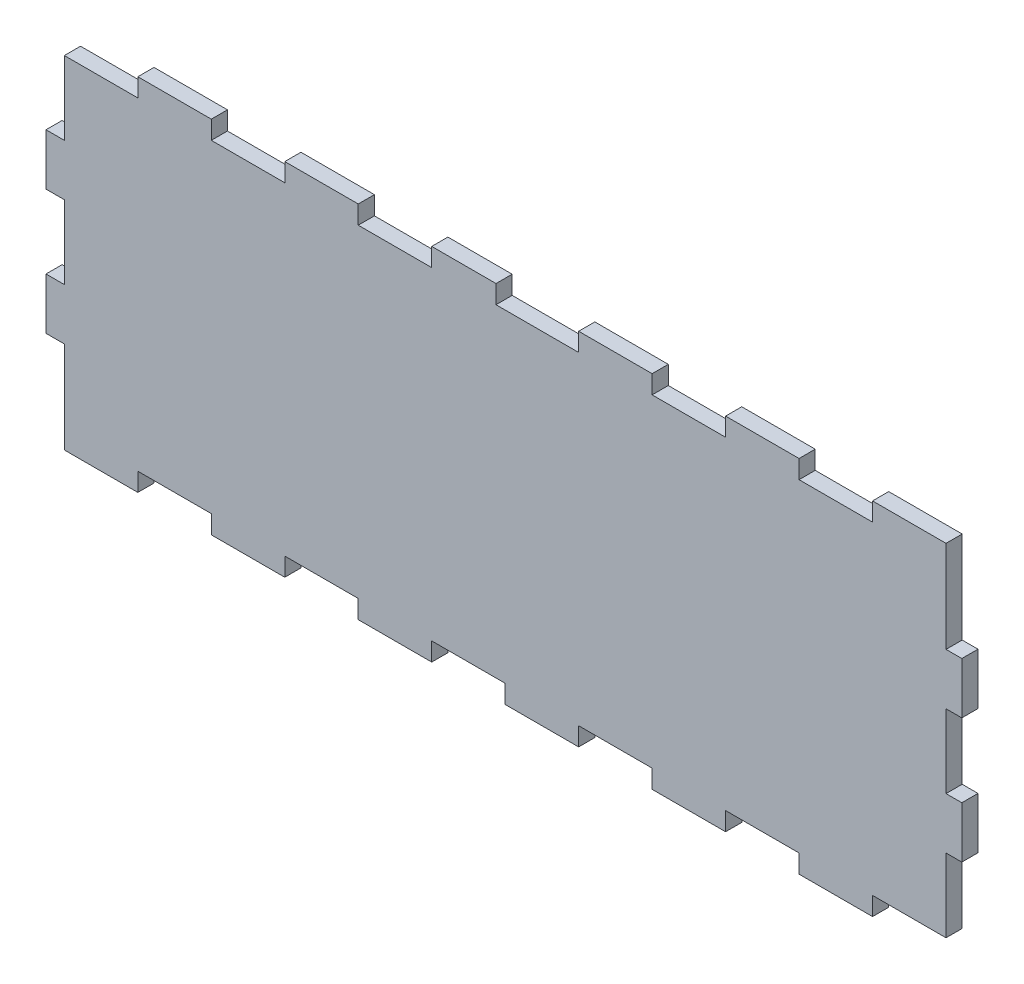
SolidWorks part; units mm, degrees
ref_plane "Front Plane" through (0, 0, 0) normal (0, 0, 1) x (1, 0, 0)
ref_plane "Top Plane" through (0, 0, 0) normal (0, 1, 0) x (1, 0, 0)
ref_plane "Right Plane" through (0, 0, 0) normal (1, 0, 0) x (0, 0, -1)
sketch "Sketch1" plane through (-5.3296, -16.203, 0) normal (0, 0, 1) x (1, 0, 0)
  line L0 (-139.4125, -47.1311) -> (-139.4125, -165.2411) construction
  line L1 (-294.9875, -47.1311) -> (-294.9875, -40.7811) construction
  line L2 (-294.9875, -47.1311) -> (-294.9875, -165.2411)
  line L3 (-294.9875, -165.2411) -> (16.1625, -165.2411)
  line L4 (16.1625, -158.8911) -> (16.1625, -165.2411)
  line L5 (-139.4125, -47.1311) -> (16.1625, -47.1311)
  line L6 (-294.9875, -158.8911) -> (16.1625, -158.8911)
  line L7 (16.1625, -47.1311) -> (16.1625, -158.8911)
  line L8 (-139.4125, -47.1311) -> (-294.9875, -47.1311)
  line L9 (-139.4125, -40.7811) -> (16.1625, -40.7811)
  line L10 (16.1625, -40.7811) -> (16.1625, -47.1311)
  line L11 (-139.4125, -47.1311) -> (-139.4125, -40.7811)
  line L12 (-139.4125, -40.7811) -> (-288.6375, -40.7811)
  line L13 (-288.6375, -165.2411) -> (-288.6375, -40.7811)
  line L14 (-136.2375, -47.1311) -> (-139.4125, -47.1311)
  line L15 (16.1625, -47.1311) -> (21.6327, -47.1311)
  line L16 (16.1625, -47.1311) -> (16.1625, -158.8911)
  line L17 (16.1625, -158.8911) -> (21.6327, -158.8911)
  line L18 (21.6327, -47.1311) -> (21.6327, -158.8911)
  line L19 (16.1625, -47.1311) -> (21.6327, -47.1311)
  line L20 (16.1625, -47.1311) -> (16.1625, -72.5311)
  line L21 (-288.6375, -165.2411) -> (-263.2375, -165.2411)
  line L22 (-288.6375, -165.2411) -> (-288.6375, -158.8911)
  line L23 (-288.6375, -158.8911) -> (-263.2375, -158.8911)
  line L24 (-263.2375, -165.2411) -> (-263.2375, -158.8911)
  line L25 (-237.8375, -158.8911) -> (-212.4375, -158.8911)
  line L26 (-237.8375, -158.8911) -> (-237.8375, -165.2411)
  line L27 (-237.8375, -165.2411) -> (-212.4375, -165.2411)
  line L28 (-212.4375, -158.8911) -> (-212.4375, -165.2411)
  line L29 (-187.0375, -158.8911) -> (-161.6375, -158.8911)
  line L30 (-187.0375, -158.8911) -> (-187.0375, -165.2411)
  line L31 (-187.0375, -165.2411) -> (-161.6375, -165.2411)
  line L32 (-161.6375, -158.8911) -> (-161.6375, -165.2411)
  line L33 (-136.2375, -158.8911) -> (-110.8375, -158.8911)
  line L34 (-136.2375, -158.8911) -> (-136.2375, -165.2411)
  line L35 (-136.2375, -165.2411) -> (-110.8375, -165.2411)
  line L36 (-110.8375, -158.8911) -> (-110.8375, -165.2411)
  line L37 (-85.4375, -158.8911) -> (-60.0375, -158.8911)
  line L38 (-85.4375, -158.8911) -> (-85.4375, -165.2411)
  line L39 (-85.4375, -165.2411) -> (-60.0375, -165.2411)
  line L40 (-60.0375, -158.8911) -> (-60.0375, -165.2411)
  line L41 (-34.6375, -158.8911) -> (-9.2375, -158.8911)
  line L42 (-34.6375, -158.8911) -> (-34.6375, -165.2411)
  line L43 (-34.6375, -165.2411) -> (-9.2375, -165.2411)
  line L44 (-9.2375, -158.8911) -> (-9.2375, -165.2411)
  line L45 (-294.9875, -47.1311) -> (-288.6375, -47.1311)
  line L46 (-294.9875, -47.1311) -> (-294.9875, -72.5311)
  line L47 (-294.9875, -72.5311) -> (-288.6375, -72.5311)
  line L48 (-288.6375, -47.1311) -> (-288.6375, -72.5311)
  line L49 (-294.9875, -90.3111) -> (-288.6375, -90.3111)
  line L50 (-294.9875, -90.3111) -> (-294.9875, -115.7111)
  line L51 (-294.9875, -115.7111) -> (-288.6375, -115.7111)
  line L52 (-288.6375, -90.3111) -> (-288.6375, -115.7111)
  line L53 (-294.9875, -133.4911) -> (-288.6375, -133.4911)
  line L54 (-294.9875, -133.4911) -> (-294.9875, -158.8911)
  line L55 (-294.9875, -158.8911) -> (-288.6375, -158.8911)
  line L56 (-288.6375, -133.4911) -> (-288.6375, -158.8911)
  line L57 (16.1625, -72.5311) -> (21.6327, -72.5311)
  line L58 (21.6327, -47.1311) -> (21.6327, -72.5311)
  line L59 (16.1625, -90.3111) -> (21.6327, -90.3111)
  line L60 (16.1625, -90.3111) -> (16.1625, -115.7111)
  line L61 (16.1625, -115.7111) -> (21.6327, -115.7111)
  line L62 (21.6327, -90.3111) -> (21.6327, -115.7111)
  line L63 (21.6327, -158.8911) -> (16.1625, -158.8911)
  line L64 (21.6327, -158.8911) -> (21.6327, -133.4911)
  line L65 (21.6327, -133.4911) -> (16.1625, -133.4911)
  line L66 (16.1625, -158.8911) -> (16.1625, -133.4911)
  line L67 (-288.6375, -40.7811) -> (-263.2375, -40.7811)
  line L68 (-288.6375, -40.7811) -> (-288.6375, -47.1311)
  line L69 (-288.6375, -47.1311) -> (-263.2375, -47.1311)
  line L70 (-263.2375, -40.7811) -> (-263.2375, -47.1311)
  line L71 (-237.8375, -40.7811) -> (-212.4375, -40.7811)
  line L72 (-237.8375, -40.7811) -> (-237.8375, -47.1311)
  line L73 (-237.8375, -47.1311) -> (-212.4375, -47.1311)
  line L74 (-212.4375, -40.7811) -> (-212.4375, -47.1311)
  line L75 (-187.0375, -40.7811) -> (-161.6375, -40.7811)
  line L76 (-187.0375, -40.7811) -> (-187.0375, -47.1311)
  line L77 (-187.0375, -47.1311) -> (-161.6375, -47.1311)
  line L78 (-161.6375, -40.7811) -> (-161.6375, -47.1311)
  line L79 (-136.2375, -40.7811) -> (-110.8375, -40.7811)
  line L80 (-136.2375, -40.7811) -> (-136.2375, -47.1311)
  line L81 (-136.2375, -47.1311) -> (-110.8375, -47.1311)
  line L82 (-110.8375, -40.7811) -> (-110.8375, -47.1311)
  line L83 (-85.4375, -40.7811) -> (-60.0375, -40.7811)
  line L84 (-85.4375, -40.7811) -> (-85.4375, -47.1311)
  line L85 (-85.4375, -47.1311) -> (-60.0375, -47.1311)
  line L86 (-60.0375, -40.7811) -> (-60.0375, -47.1311)
  line L87 (-34.6375, -40.7811) -> (-9.2375, -40.7811)
  line L88 (-34.6375, -40.7811) -> (-34.6375, -47.1311)
  line L89 (-34.6375, -47.1311) -> (-9.2375, -47.1311)
  line L90 (-9.2375, -40.7811) -> (-9.2375, -47.1311)
  line L91 (-139.4125, -40.7811) -> (-136.2375, -40.7811)
  point P32 (-161.6375, -162.0661)
  dimension "D1" = 6.35
  dimension "D2" = 311.15
  dimension "D3" = 6.35
  dimension "D4" = 6.35
  dimension "D5" = 6.35
  dimension "D6" = 124.46
  dimension "D7" = 25.4
  dimension "D8" = 25.4
  dimension "D9" = 25.4
  dimension "D10" = 25.4
  dimension "D11" = 25.4
  dimension "D12" = 25.4
  dimension "D13" = 25.4
  dimension "D14" = 25.4
  dimension "D15" = 25.4
  dimension "D16" = 25.4
  dimension "D17" = 25.4
  dimension "D18" = 25.4
  dimension "D19" = 25.4
  dimension "D20" = 25.4
  dimension "D21" = 17.78
  dimension "D22" = 111.76
extrude "Boss-Extrude1" add sketch "Sketch1" along normal blind 5.588
